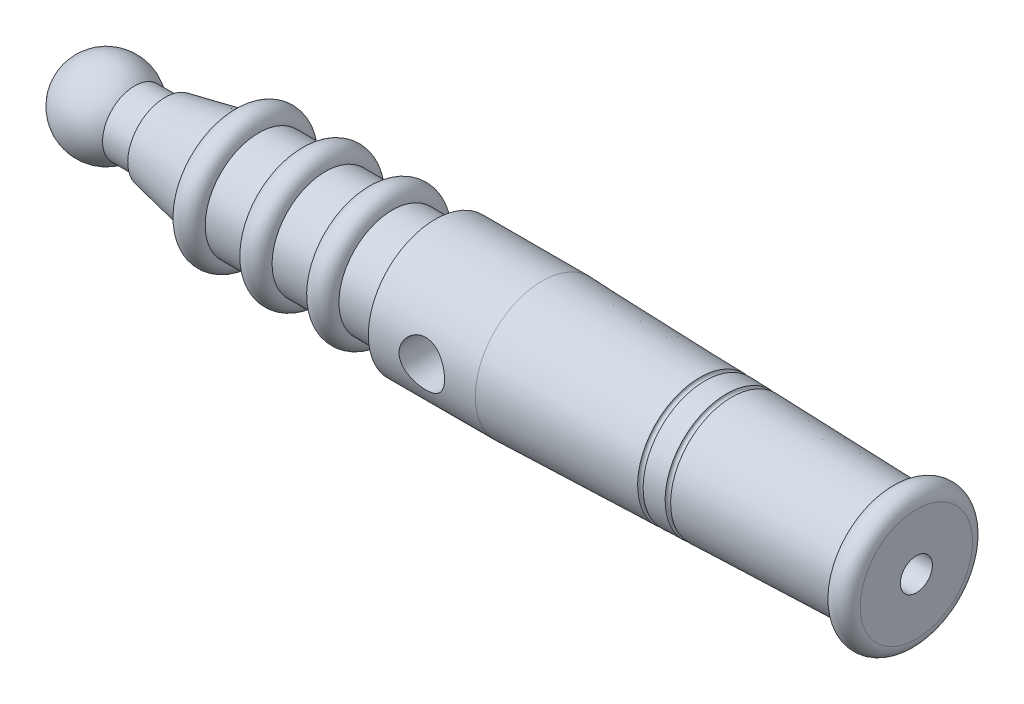
SolidWorks part; units mm, degrees
ref_plane "Front Plane" through (0, 0, 0) normal (0, 0, 1) x (1, 0, 0)
ref_plane "Top Plane" through (0, 0, 0) normal (0, 1, 0) x (1, 0, 0)
ref_plane "Right Plane" through (0, 0, 0) normal (1, 0, 0) x (0, 0, -1)
sketch "Sketch2" plane through (0, 0, 0) normal (0, 0, 1) x (1, 0, 0)
  line L0 (0, 0) -> (109.4989, 0)
  line L1 (109.4989, 0) -> (109.4989, 3)
  line L2 (109.4989, 3) -> (159.4989, 3)
  line L5 (154.5, 10.574) -> (124.9842, 11.4486)
  line L6 (89.5, 12.5) -> (69.5, 12.5)
  line L7 (69.5, 12.5) -> (69.5, 10)
  line L8 (56.5, 10) -> (49.0329, 10)
  line L9 (31.5485, 9.5097) -> (19, 7)
  line L10 (19, 7) -> (19, 6)
  line L11 (19, 6) -> (13.2915, 6)
  line L12 (159.4989, 10.5) -> (159.4989, 3)
  line L13 (36.5, 10) -> (44, 10)
  line L14 (61.5, 10) -> (69.5, 10)
  line L15 (118.9873, 11.6263) -> (89.5, 12.5)
  line L16 (123.9851, 11.4782) -> (119.9864, 11.5967)
  line L17 (154.5, 10.574) -> (156.9989, 10.5) construction
  line L18 (156.9989, 10.5) -> (159.4989, 10.5) construction
  line L19 (49, 10) -> (49.0329, 10)
  arc A0 (0, 0) -> (13.2915, 6) centre (8, 0) cw
  arc A1 (159.4989, 10.5) -> (154.5, 10.574) centre (156.9989, 10.5) ccw
  arc A2 (61.5, 10) -> (56.5, 10) centre (59, 10) ccw
  arc A3 (49, 10) -> (44, 10) centre (46.5, 10) ccw
  arc A4 (36.5, 10) -> (31.5485, 9.5097) centre (34, 10) ccw
  arc A5 (124.9842, 11.4486) -> (123.9851, 11.4782) centre (124.4842, 11.4486) cw
  arc A6 (119.9864, 11.5967) -> (118.9873, 11.6263) centre (119.4864, 11.5967) cw
  point P18 (16.1458, 6)
  dimension "D3" = 2.5
  dimension "D4" = 7.5
  dimension "D8" = 8
  dimension "D15" = 2.5
  dimension "D20" = 0.5
  dimension "D1" = 50
  dimension "D2" = 3
  dimension "D5" = 20
  dimension "D6" = 65
  dimension "D7" = 11
  dimension "D9" = 35.5
  dimension "D10" = 6
  dimension "D11" = 7
  dimension "D12" = 10
  dimension "D13" = 12.5
  dimension "D14" = 15
  dimension "D16" = 10
  dimension "D17" = 8
  dimension "D18" = 20
  dimension "D19" = 5
  dimension "D21" = 30
revolve "Revolve1" add sketch "Sketch2" angle 360 about L0
sketch "Sketch3" plane through (0, 0, 0) normal (0, 0, 1) x (1, 0, 0)
  circle A0 centre (79.5, 0) radius 4.25
  point P2 (0, 0)
  dimension "D1" = 8.5
  dimension "D2" = 10
extrude "Cut-Extrude7" cut sketch "Sketch3" against normal through all both and the other way through all contours A0
